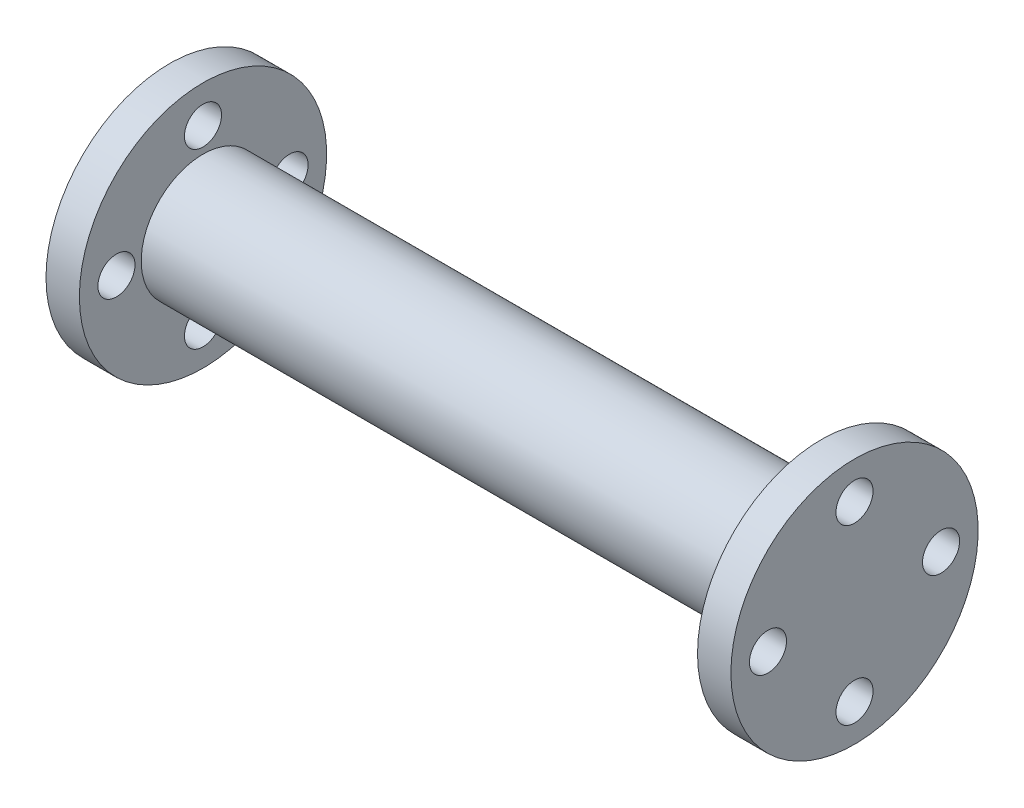
SolidWorks part; units mm, degrees
ref_plane "Alzado" through (0, 0, 0) normal (0, 0, 1) x (1, 0, 0)
ref_plane "Planta" through (0, 0, 0) normal (0, 1, 0) x (1, 0, 0)
ref_plane "Vista lateral" through (0, 0, 0) normal (1, 0, 0) x (0, 0, -1)
sketch "Croquis1" plane through (0, 0, 0) normal (1, 0, 0) x (0, 0, -1)
  circle A0 centre (0, 0) radius 10
extrude "Saliente-Extruir1" add sketch "Croquis1" along normal blind 2.7
sketch "Croquis2" plane through (2.7, 0, 0) normal (1, 0, 0) x (0, 0, -1)
  circle A0 centre (0, 0) radius 5
extrude "Saliente-Extruir2" add sketch "Croquis2" along normal blind 50
sketch "Croquis3" plane through (52.7, 0, 0) normal (1, 0, 0) x (0, 0, -1)
  circle A0 centre (0, 0) radius 10
extrude "Saliente-Extruir3" add sketch "Croquis3" along normal blind 2.7
sketch "Croquis5" plane through (55.4, 0, 0) normal (1, 0, 0) x (0, 0, -1)
  line L0 (0, 0) -> (0, 7) construction
  circle A0 centre (0, 7) radius 1.5
  circle A1 centre (7, 0) radius 1.5
  circle A2 centre (0, -7) radius 1.5
  circle A3 centre (-7, 0) radius 1.5
  point P13 (0, 0)
  dimension "D1" = 4
extrude "Cortar-Extruir1" cut sketch "Croquis5" against normal blind 60
